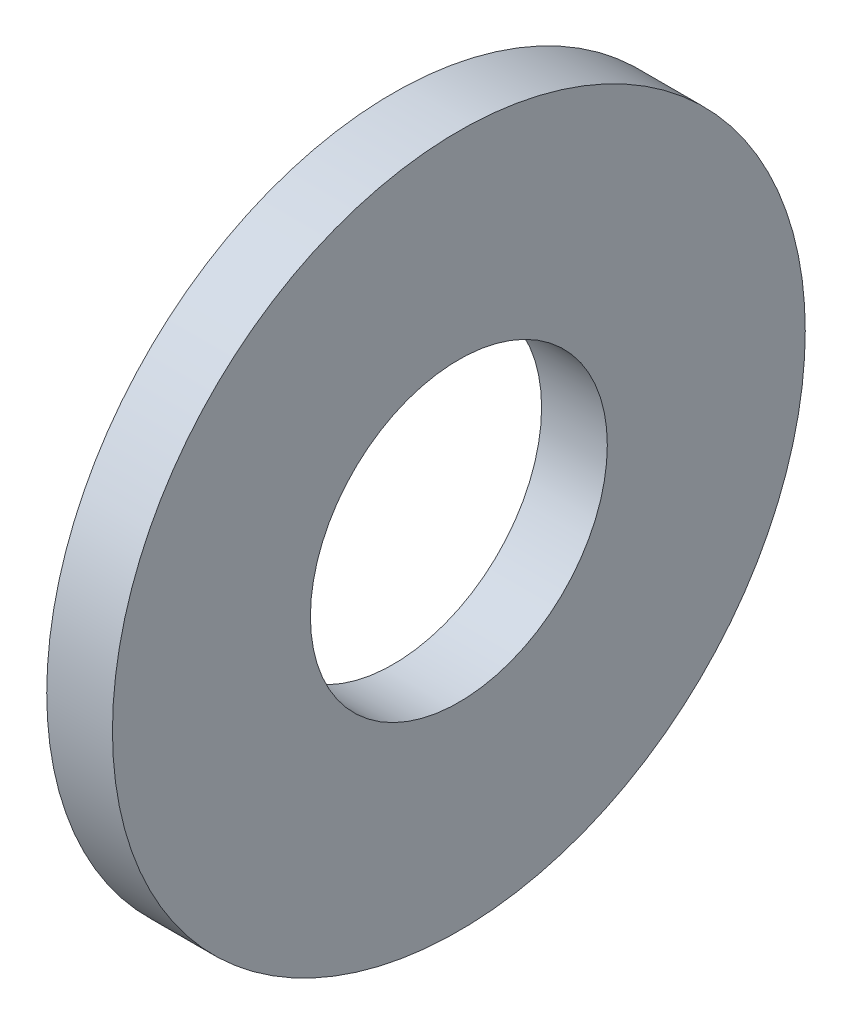
SolidWorks part; units mm, degrees
ref_plane "Front Plane" through (0, 0, 0) normal (0, 0, 1) x (1, 0, 0)
ref_plane "Top Plane" through (0, 0, 0) normal (0, 1, 0) x (1, 0, 0)
ref_plane "Right Plane" through (0, 0, 0) normal (1, 0, 0) x (0, 0, -1)
sketch "Sketch1" plane through (0, 0, 0) normal (1, 0, 0) x (0, 0, -1)
  circle A0 centre (0, 0) radius 11.1125
  circle A1 centre (0, 0) radius 4.7625
  dimension "OD" = 22.225
  dimension "ID" = 9.525
extrude "Boss-Extrude1" add sketch "Sketch1" along normal blind 2.1082
